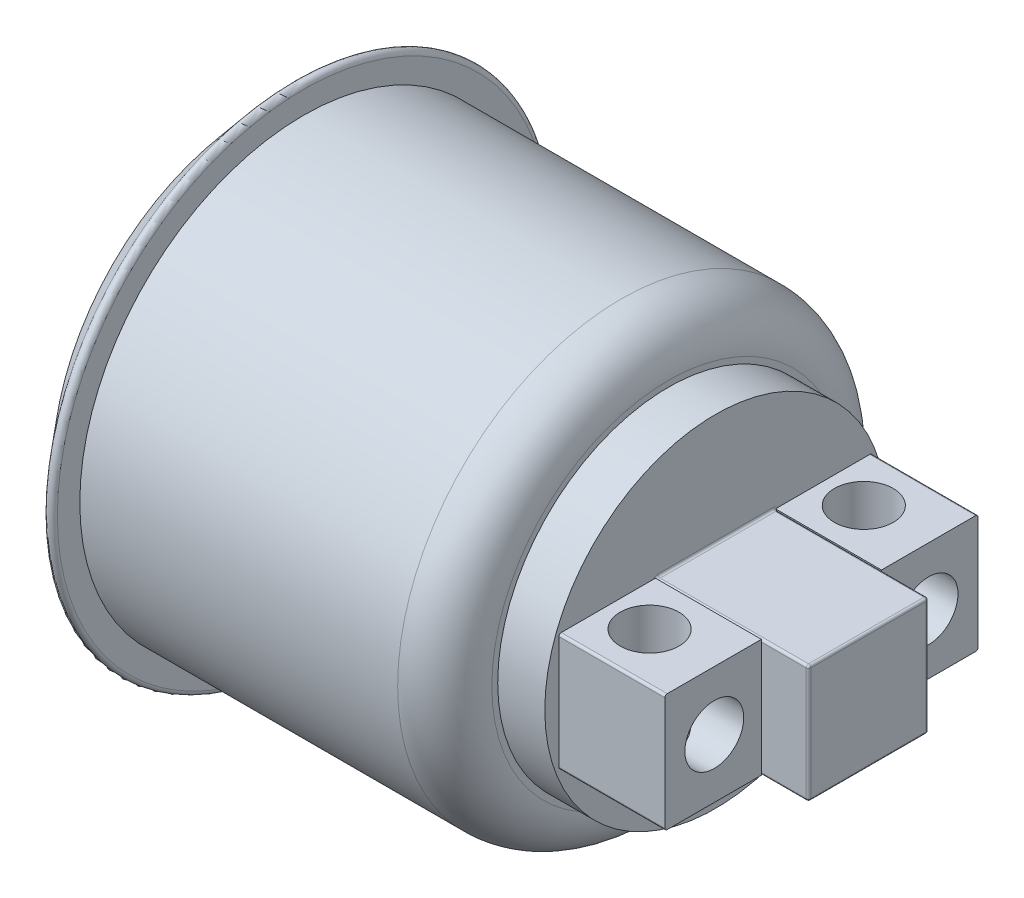
SolidWorks part; units mm, degrees
ref_plane "Спереди" through (0, 0, 0) normal (0, 0, 1) x (1, 0, 0)
ref_plane "Сверху" through (0, 0, 0) normal (0, 1, 0) x (1, 0, 0)
ref_plane "Справа" through (0, 0, 0) normal (1, 0, 0) x (0, 0, -1)
sketch "Эскиз1" plane through (0, 0, 0) normal (0, 1, 0) x (1, 0, 0)
  line L0 (1.9, 9.5) -> (1.9, 11)
  line L1 (1.9, 0) -> (17.4, 0)
  line L3 (1.9, 9.5) -> (17.4, 9.5)
  line L4 (17.4, 0) -> (17.4, 9.5)
  line L5 (1.9, 11) -> (0, 8.75)
  line L6 (0, 8.75) -> (0, 0)
  line L7 (0, 0) -> (1.9, 0)
  line L8 (0, 0) -> (17.4, 0) construction
  dimension "D1" = 9.5
  dimension "D2" = 15.5
  dimension "D4" = 11
  dimension "D5" = 8.75
revolve "Повернуть1" add sketch "Эскиз1" angle 360 about L8
sketch "Эскиз2" plane through (0, 0, 0) normal (-1, 0, 0) x (0, 0, 1)
  circle A0 centre (0, 0) radius 7.51
  circle A1 centre (0, 0) radius 7.5
  dimension "D1" = 0.01
  dimension "D2" = 15
extrude "Вырез-Вытянуть1" cut sketch "Эскиз2" against normal blind 0.1
fillet "Скругление1" radius 2 1 edges at (17.4, 0, 9.5)
sketch "Эскиз3" plane through (17.4, 0, 0) normal (1, 0, 0) x (0, 0, -1)
  circle A0 centre (0, 0) radius 7.25
  dimension "D1" = 14.5
extrude "Бобышка-Вытянуть1" add sketch "Эскиз3" along normal blind 2
sketch "Эскиз4" plane through (19.4, 0, 0) normal (1, 0, 0) x (0, 0, -1)
  line L1 (0, 2.5) -> (2.55, 2.5)
  line L2 (0, 2.5) -> (0, -2.5)
  line L3 (0, -2.5) -> (2.55, -2.5)
  line L4 (2.55, 2.5) -> (2.55, -2.5)
  line L5 (0, 2.5) -> (-2.55, 2.5)
  line L6 (0, 2.5) -> (0, -2.5)
  line L7 (0, -2.5) -> (-2.55, -2.5)
  line L8 (-2.55, 2.5) -> (-2.55, -2.5)
  dimension "D1" = 5.1
  dimension "D2" = 2.55
  dimension "D3" = 2.5
  dimension "D4" = 2.55
  dimension "D5" = 5
extrude "Бобышка-Вытянуть2" add sketch "Эскиз4" along normal blind 6.5 contours L4 L1 L2 L3 | L5 L8 L7 L2
sketch "Эскиз5" plane through (19.4, 0, 0) normal (1, 0, 0) x (0, 0, -1)
  line L0 (2.55, 2.5) -> (2.55, -2.5) construction
  line L1 (-2.55, 2.5) -> (-6.65, 2.5)
  line L2 (-2.55, 2.5) -> (-2.55, -2.5)
  line L3 (-2.55, -2.5) -> (-6.65, -2.5)
  line L4 (-6.65, 2.5) -> (-6.65, -2.5)
  line L5 (2.55, 2.5) -> (6.65, 2.5)
  line L6 (2.55, 2.5) -> (2.55, -2.5)
  line L7 (2.55, -2.5) -> (6.65, -2.5)
  line L8 (6.65, 2.5) -> (6.65, -2.5)
  dimension "D1" = 4.1
  dimension "D2" = 4.1
extrude "Бобышка-Вытянуть4" add sketch "Эскиз5" along normal blind 4.5 separate body
fillet "Скругление2" radius 0.1 1 edges at (21.65, -2.5, -6.65)
fillet "Скругление4" radius 0.1 2 edges at (21.65, 2.5, 6.65) (21.65, -2.5, 6.65)
fillet "Скругление5" radius 0.1 1 edges at (21.65, 2.5, -6.65)
sketch "Эскиз6" plane through (23.9, 0, 0) normal (1, 0, 0) x (0, 0, -1)
  line L0 (4.55, 2.5) -> (4.55, -2.5) construction
  line L1 (-6.65, 0) -> (6.65, 0) construction
  line L2 (-6.65, 2.4) -> (-6.65, -2.4) construction
  line L3 (6.65, -2.4) -> (6.65, 2.4) construction
  line L4 (-4.55, 2.5) -> (-4.55, -2.5) construction
  line L5 (-2.55, 2.5) -> (-6.55, 2.5) construction
  line L6 (-6.55, -2.5) -> (-2.55, -2.5) construction
  line L7 (6.55, 2.5) -> (2.55, 2.5) construction
  line L8 (2.55, -2.5) -> (6.55, -2.5) construction
  circle A0 centre (-4.55, 0) radius 1.25
  circle A1 centre (4.55, 0) radius 1.25
  point P16 (-4.55, 0)
  point P23 (4.55, 0)
  dimension "D1" = 2.5
  dimension "D2" = 2.5
extrude "Вырез-Вытянуть3" cut sketch "Эскиз6" against normal blind 2.7
sketch "Эскиз7" plane through (0, 2.5, 0) normal (0, 1, 0) x (1, 0, 0)
  line L0 (19.9, 6.55) -> (19.9, -6.55) construction
  line L1 (23.9, 6.55) -> (19.4, 6.55) construction
  line L2 (19.4, -6.55) -> (23.9, -6.55) construction
  line L3 (23.9, 6.55) -> (23.9, 2.55) construction
  line L4 (23.9, 4.55) -> (19.4, 4.55) construction
  line L5 (19.4, 6.55) -> (19.4, 2.55) construction
  line L6 (23.9, -4.55) -> (19.4, -4.55) construction
  line L7 (23.9, -2.55) -> (23.9, -6.55) construction
  line L8 (19.4, -2.55) -> (19.4, -6.55) construction
  circle A0 centre (21.15, 4.55) radius 1.25
  circle A1 centre (21.15, -4.55) radius 1.25
  dimension "D2" = 2.5
  dimension "D3" = 2.5
  dimension "D1" = 4
extrude "Вырез-Вытянуть4" cut sketch "Эскиз7" against normal through all
fillet "Скругление7" radius 0.1 12 edges at (19.4, -2.5, 0) (19.4, 2.5, 0) (25.9, -2.5, 0) (25.9, 2.5, 0) (22.65, 2.5, 2.55) (19.4, 0, 2.55) (25.9, 0, 2.55) (22.65, -2.5, 2.55) (22.65, -2.5, -2.55) (19.4, 0, -2.55) (25.9, 0, -2.55) (22.65, 2.5, -2.55)
fillet "Скругление8" radius 0.2 1 edges at (1.9, 0, 11)
